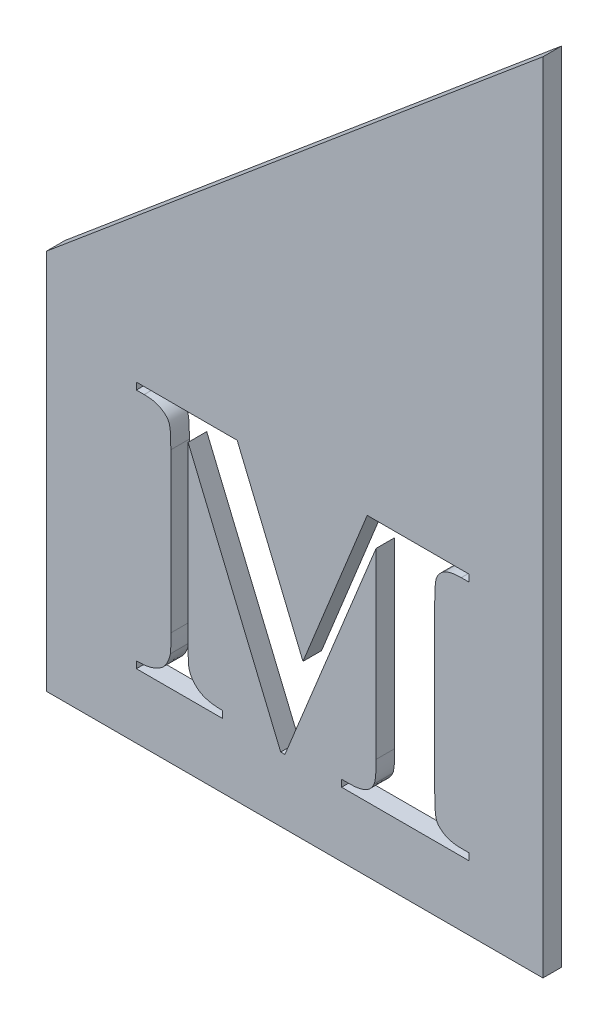
SolidWorks part; units mm, degrees
ref_plane "Front Plane" through (0, 0, 0) normal (0, 0, 1) x (1, 0, 0)
ref_plane "Top Plane" through (0, 0, 0) normal (0, 1, 0) x (1, 0, 0)
ref_plane "Right Plane" through (0, 0, 0) normal (1, 0, 0) x (0, 0, -1)
sketch "Sketch1" plane through (0, 0, 0) normal (0, 0, 1) x (1, 0, 0)
  line L0 (0, 0) -> (46.6039, 0) construction
  line L1 (0, 0) -> (222.1529, 186.4084) construction
  line L2 (73.2089, 61.4296) -> (153.2089, 128.5575)
  line L3 (153.2089, 128.5575) -> (153.2089, 0)
  line L4 (153.2089, 0) -> (73.2089, 0)
  line L5 (73.2089, 61.4296) -> (73.2089, 0)
  dimension "D1" = 40
  dimension "D2" = 290
  dimension "D3" = 200
  dimension "D4" = 80
extrude "Boss-Extrude1" add sketch "Sketch1" along normal blind 3
sketch "Sketch2" plane through (0, 0, 3) normal (0, 0, 1) x (1, 0, 0)
  text T0 "M" font "Times New Roman" height 40
extrude "Cut-Extrude1" cut sketch "Sketch2" against normal blind 3
